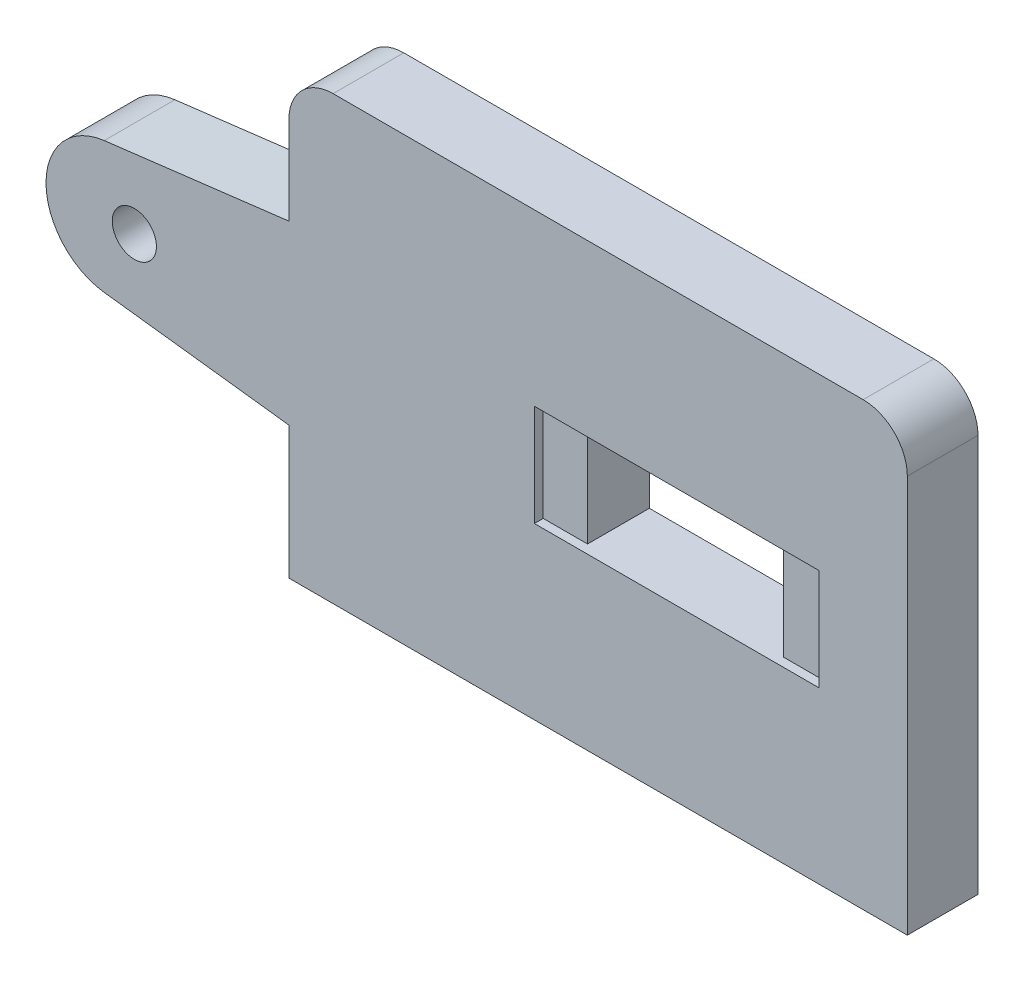
SolidWorks part; units mm, degrees
ref_plane "Front Plane" through (0, 0, 0) normal (0, 0, 1) x (1, 0, 0)
ref_plane "Top Plane" through (0, 0, 0) normal (0, 1, 0) x (1, 0, 0)
ref_plane "Right Plane" through (0, 0, 0) normal (1, 0, 0) x (0, 0, -1)
sketch "Sketch1" plane through (0, 0, 0) normal (0, 0, 1) x (1, 0, 0)
  line L0 (-35, 10) -> (-55.9098, 7.4446)
  line L1 (-30, 25) -> (30, 25)
  line L2 (-35, 20) -> (-35, 10)
  line L3 (-35, -25) -> (35, -25)
  line L4 (35, 20) -> (35, -25)
  line L5 (-35, 25) -> (35, -25) construction
  line L6 (-35, -25) -> (35, 25) construction
  line L7 (-35, -10) -> (-55.9098, -7.4446)
  line L8 (-35, -10) -> (-35, -25)
  arc A0 (-30, 25) -> (-35, 20) centre (-30, 20) ccw
  arc A1 (30, 25) -> (35, 20) centre (30, 20) cw
  circle A2 centre (-55, 0) radius 7.5
  point P0 (0, 0)
  dimension "D3" = 5
  dimension "D4" = 5
  dimension "D5" = 15
  dimension "D1" = 70
  dimension "D2" = 50
  dimension "D6" = 20
  dimension "D7" = 15
  dimension "D8" = 15
extrude "Boss-Extrude1" add sketch "Sketch1" along normal blind 8
sketch "Sketch3" plane through (0, 0, 8) normal (0, 0, 1) x (1, 0, 0)
  line L0 (35, 20) -> (35, -25) construction
  line L1 (-2.2, 5.75) -> (20, 5.75)
  line L2 (-2.2, 5.75) -> (-2.2, -5.75)
  line L3 (-2.2, -5.75) -> (20, -5.75)
  line L4 (20, 5.75) -> (20, -5.75)
  line L5 (-2.2, 5.75) -> (20, -5.75) construction
  line L6 (-2.2, -5.75) -> (20, 5.75) construction
  point P0 (8.9, 0)
  dimension "D1" = 15
  dimension "D2" = 11.5
  dimension "D3" = 22.2
extrude "Cut-Extrude1" cut sketch "Sketch3" against normal blind 8
sketch "Sketch4" plane through (0, 0, 8) normal (0, 0, 1) x (1, 0, 0)
  line L0 (20, -5.75) -> (14.25, -5.75)
  line L1 (14.25, -5.75) -> (-2.2, -5.75)
  line L2 (-2.2, -5.75) -> (-2.2, 5.75)
  line L3 (14.25, 5.75) -> (-2.2, 5.75)
  line L4 (20, 5.75) -> (14.25, 5.75)
  line L5 (20, 5.75) -> (20, -5.75)
  circle A0 centre (14.25, 0) radius 2.25
  arc A1 (8.8413, 1.9516) -> (8.8413, -1.9516) centre (8.25, 0) ccw
  arc A2 (8.8413, -1.9516) -> (8.8413, 1.9516) centre (14.25, 0) ccw
  circle A3 centre (-52.5, 0) radius 2.5
  arc A4 (-55.9098, 7.4446) -> (-55.9098, -7.4446) centre (-55, 0) ccw construction
  point P18 (-62.5, 0)
  dimension "D3" = 4.5
  dimension "D4" = 2.0392
  dimension "D5" = 5.75
  dimension "D11" = 90
  dimension "D17" = 5
  dimension "D1" = 16.45
  dimension "D2" = 5.75
  dimension "D6" = 5.75
  dimension "D7" = 5.75
  dimension "D8" = 16.45
  dimension "D9" = 5.75
  dimension "D10" = 5.75
  dimension "D12" = 90
  dimension "D13" = 90
  dimension "D14" = 11.5
  dimension "D15" = 6
  dimension "D16" = 10.45
  dimension "D18" = 10
extrude "Cut-Extrude2" cut sketch "Sketch4" against normal blind 20 contours A3
sketch "Sketch6" plane through (0, 0, 8) normal (0, 0, 1) x (1, 0, 0)
  line L0 (20, 5.75) -> (25.0147, 5.75)
  line L1 (25.0147, 5.75) -> (25.0147, -5.75)
  line L2 (25.0147, -5.75) -> (20, -5.75)
  line L3 (20, -5.75) -> (20, 5.75)
  line L4 (8.9, 5.75) -> (8.9, -5.75)
  line L5 (20, 5.75) -> (-2.2, 5.75) construction
  line L6 (-2.2, -5.75) -> (20, -5.75) construction
  line L7 (-7.2147, -5.75) -> (-2.2, -5.75)
  line L8 (-7.2147, 5.75) -> (-7.2147, -5.75)
  line L9 (-2.2, 5.75) -> (-7.2147, 5.75)
  line L10 (-2.2, -5.75) -> (-2.2, 5.75)
  line M7 (20, 5.75) -> (20, -5.75)
  line M9 (-2.2, -5.75) -> (-2.2, 5.75)
extrude "Cut-Extrude3" cut sketch "Sketch6" against normal blind 1 contours L9 L8 L7 M9 | L2 L1 L0 M7
